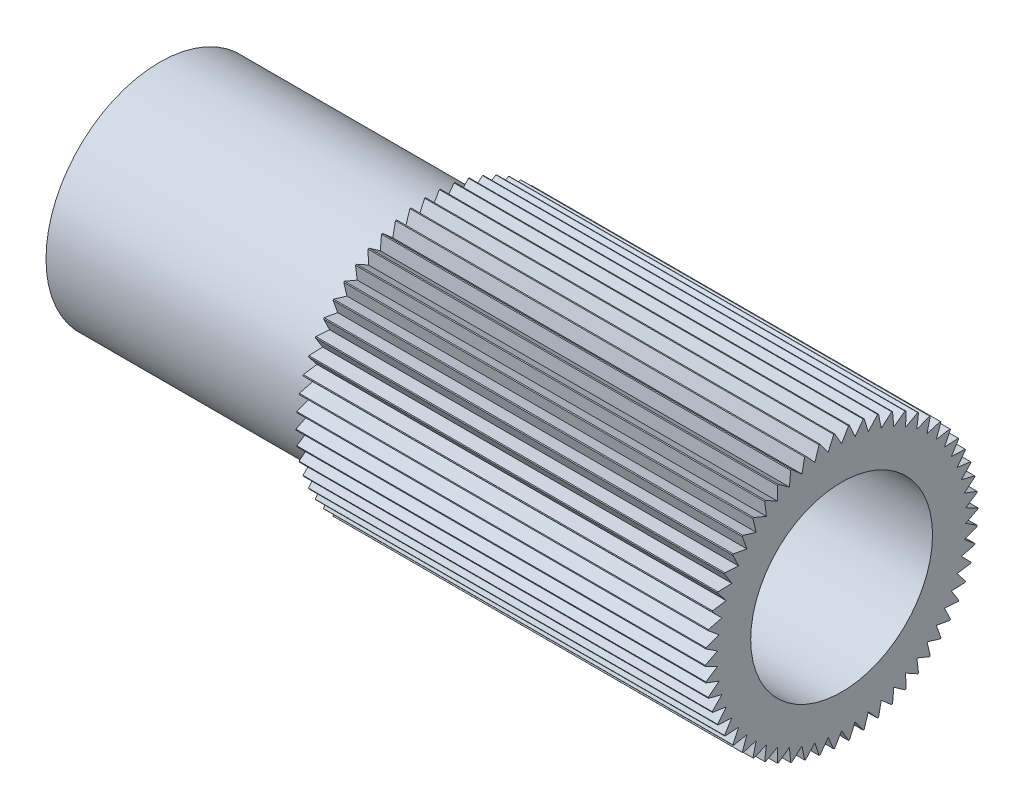
SolidWorks part; units mm, degrees
ref_plane "Alzado" through (0, 0, 0) normal (0, 0, 1) x (1, 0, 0)
ref_plane "Planta" through (0, 0, 0) normal (0, 1, 0) x (1, 0, 0)
ref_plane "Vista lateral" through (0, 0, 0) normal (1, 0, 0) x (0, 0, -1)
sketch "Croquis1" plane through (0, 0, 0) normal (1, 0, 0) x (0, 0, -1)
  circle A3 centre (0, 0) radius 1.5
  dimension "D1" = 3
extrude "Extruir1" add sketch "Croquis1" along normal blind 4.5
sketch "Croquis3" plane through (0, 0, 0) normal (-1, 0, 0) x (0, 0, 1)
  circle A0 centre (0, 0) radius 1.25
  dimension "D1" = 2.5
extrude "Extruir2" add sketch "Croquis3" along normal blind 3
sketch "Croquis4" plane through (4.5, 0, 0) normal (1, 0, 0) x (0, 0, -1)
  circle A0 centre (0, 0) radius 1
  dimension "D1" = 2
extrude "Extruir3" cut sketch "Croquis4" against normal blind 4
sketch "Croquis6" plane through (4.5, 0, 0) normal (1, 0, 0) x (0, 0, -1)
  line L0 (0, 1.3665) -> (-0.0759, 1.4981)
  line L1 (0, 1.3665) -> (0.076, 1.4981)
  circle A0 centre (0, 0) radius 1 construction
  circle A1 centre (0, 0) radius 1.5 construction
  arc A2 (0.076, 1.4981) -> (-0.0759, 1.4981) centre (0, 0) ccw
  dimension "D1" = 60
  dimension "D2" = 0.076
  dimension "D3" = 0.0759
extrude "Extruir5" cut sketch "Croquis6" against normal through all
pattern_circular "MatrizC1" count 58 over 360 about axis through (0, 0, 0) along (1, 0, 0) of "Extruir5"
